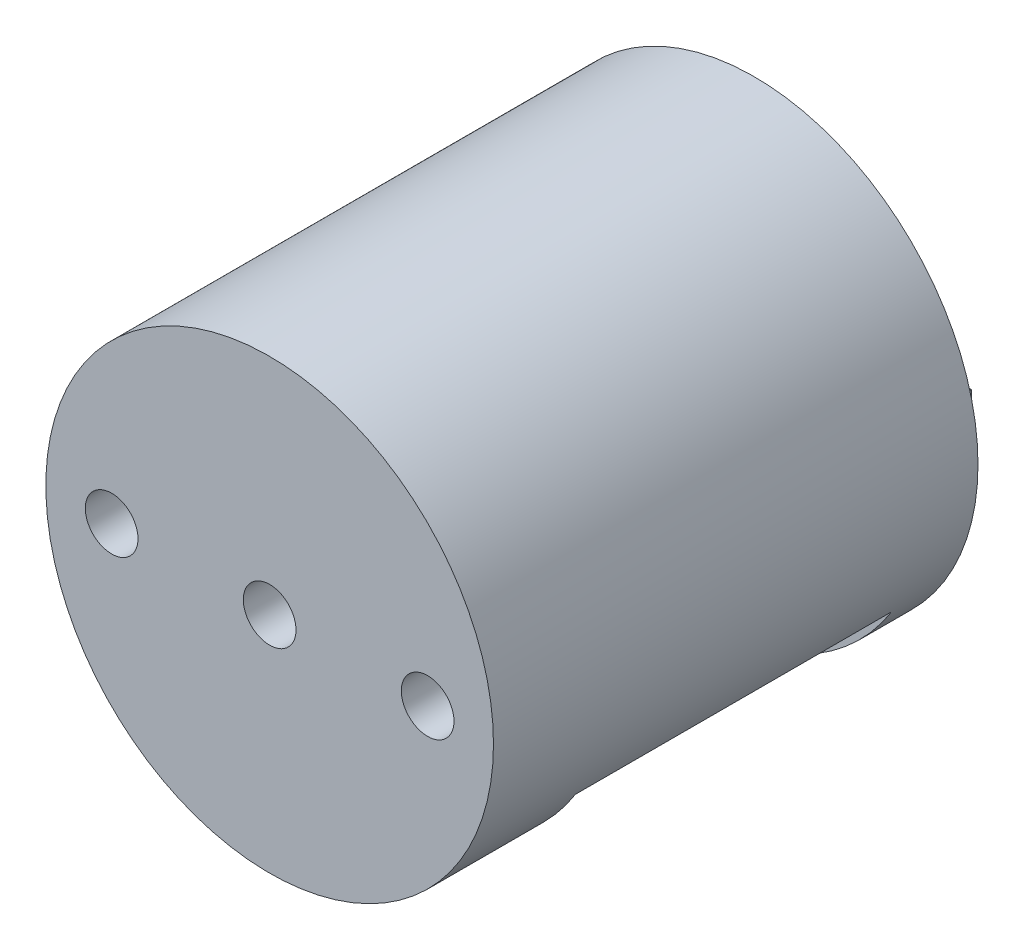
SolidWorks part; units mm, degrees
ref_plane "Plan de face" through (0, 0, 0) normal (0, 0, 1) x (1, 0, 0)
ref_plane "Plan de dessus" through (0, 0, 0) normal (0, 1, 0) x (1, 0, 0)
ref_plane "Plan de droite" through (0, 0, 0) normal (1, 0, 0) x (0, 0, -1)
sketch "Esquisse1" plane through (0, 0, 0) normal (0, 0, 1) x (1, 0, 0)
  circle A0 centre (0, 0) radius 8.5
extrude "Boss.-Extru.1" add sketch "Esquisse1" along normal blind 18.4
sketch "Esquisse2" plane through (0, 0, 0) normal (0, 0, -1) x (-1, 0, 0)
  line L1 (-3.2, -2.6) -> (3.2, -2.6)
  line L2 (-3.2, -2.6) -> (-3.2, -6)
  line L3 (-3.2, -6) -> (3.2, -6)
  line L4 (3.2, -2.6) -> (3.2, -6)
  dimension "D1" = 6.4
  dimension "D2" = 3.4
  dimension "D3" = 3.2
  dimension "D4" = 6
extrude "Boss.-Extru.2" add sketch "Esquisse2" along normal blind 2.6
sketch "Esquisse3" plane through (0, 0, -2.6) normal (0, 0, -1) x (-1, 0, 0)
  line L0 (-1.48, -3.1652) -> (-0.98, -3.1652)
  line L1 (-2.75, -3.1652) -> (-2.25, -3.1652)
  line L2 (-2.75, -3.1652) -> (-2.75, -3.6652)
  line L3 (-2.75, -3.6652) -> (-2.25, -3.6652)
  line L4 (-2.25, -3.1652) -> (-2.25, -3.6652)
  line L5 (-1.48, -3.1652) -> (-1.48, -3.6652)
  line L6 (-1.48, -3.6652) -> (-0.98, -3.6652)
  line L7 (-0.98, -3.1652) -> (-0.98, -3.6652)
  line L8 (-0.21, -3.1652) -> (0.29, -3.1652)
  line L9 (-0.21, -3.1652) -> (-0.21, -3.6652)
  line L10 (-0.21, -3.6652) -> (0.29, -3.6652)
  line L11 (0.29, -3.1652) -> (0.29, -3.6652)
  line L12 (1.06, -3.1652) -> (1.56, -3.1652)
  line L13 (1.06, -3.1652) -> (1.06, -3.6652)
  line L14 (1.06, -3.6652) -> (1.56, -3.6652)
  line L15 (1.56, -3.1652) -> (1.56, -3.6652)
  line L16 (2.33, -3.1652) -> (2.83, -3.1652)
  line L17 (2.33, -3.1652) -> (2.33, -3.6652)
  line L18 (2.33, -3.6652) -> (2.83, -3.6652)
  line L19 (2.83, -3.1652) -> (2.83, -3.6652)
  line L20 (-2.75, -4.4352) -> (-2.25, -4.4352)
  line L21 (-2.75, -4.4352) -> (-2.75, -4.9352)
  line L22 (-2.75, -4.9352) -> (-2.25, -4.9352)
  line L23 (-2.25, -4.4352) -> (-2.25, -4.9352)
  line L24 (-1.48, -4.4352) -> (-0.98, -4.4352)
  line L25 (-1.48, -4.4352) -> (-1.48, -4.9352)
  line L26 (-1.48, -4.9352) -> (-0.98, -4.9352)
  line L27 (-0.98, -4.4352) -> (-0.98, -4.9352)
  line L28 (-0.21, -4.4352) -> (0.29, -4.4352)
  line L29 (-0.21, -4.4352) -> (-0.21, -4.9352)
  line L30 (-0.21, -4.9352) -> (0.29, -4.9352)
  line L31 (0.29, -4.4352) -> (0.29, -4.9352)
  line L32 (1.06, -4.4352) -> (1.56, -4.4352)
  line L33 (1.06, -4.4352) -> (1.06, -4.9352)
  line L34 (1.06, -4.9352) -> (1.56, -4.9352)
  line L35 (1.56, -4.4352) -> (1.56, -4.9352)
  line L36 (2.33, -4.4352) -> (2.83, -4.4352)
  line L37 (2.33, -4.4352) -> (2.33, -4.9352)
  line L38 (2.33, -4.9352) -> (2.83, -4.9352)
  line L39 (2.83, -4.4352) -> (2.83, -4.9352)
  line L40 (-3.2, -2.6) -> (-3.2, -6) construction
  dimension "D1" = 0.5
  dimension "D2" = 5
  dimension "D4" = 0.45
  dimension "D3" = 2
extrude "Boss.-Extru.3" add sketch "Esquisse3" along normal blind 3
chamfer "Chanfrein1" distance 0.1 angle 45 40 edges at (2.5, -3.1652, -5.6) (2.25, -3.4152, -5.6) (2.5, -3.6652, -5.6) (2.75, -3.4152, -5.6) (2.5, -4.4352, -5.6) (2.25, -4.6852, -5.6) (2.5, -4.9352, -5.6) (2.75, -4.6852, -5.6) (1.23, -3.1652, -5.6) (0.98, -3.4152, -5.6) (1.23, -3.6652, -5.6) (1.48, -3.4152, -5.6) (1.23, -4.4352, -5.6) (0.98, -4.6852, -5.6) (1.23, -4.9352, -5.6) (1.48, -4.6852, -5.6) (-0.04, -3.1652, -5.6) (-0.29, -3.4152, -5.6) (-0.04, -3.6652, -5.6) (0.21, -3.4152, -5.6) (-0.04, -4.4352, -5.6) (-0.29, -4.6852, -5.6) (-0.04, -4.9352, -5.6) (0.21, -4.6852, -5.6) (-1.31, -3.1652, -5.6) (-1.56, -3.4152, -5.6) (-1.31, -3.6652, -5.6) (-1.06, -3.4152, -5.6) (-1.31, -4.4352, -5.6) (-1.56, -4.6852, -5.6) (-1.31, -4.9352, -5.6) (-1.06, -4.6852, -5.6) (-2.58, -3.1652, -5.6) (-2.83, -3.4152, -5.6) (-2.58, -3.6652, -5.6) (-2.33, -3.4152, -5.6) (-2.58, -4.4352, -5.6) (-2.83, -4.6852, -5.6) (-2.58, -4.9352, -5.6) (-2.33, -4.6852, -5.6)
ref_plane "Plan1" through (8.5, 0, 0) normal (1, 0, 0) x (0, 0, -1)
sketch "Esquisse4" plane through (8.5, 0, 0) normal (1, 0, 0) x (0, 0, -1)
  line L0 (-18.4, -8.5) -> (0, -8.5) construction
  line L1 (-14, -4.5) -> (-2, -4.5)
  line L2 (-14, -4.5) -> (-14, -8.5)
  line L3 (-14, -8.5) -> (-2, -8.5)
  line L4 (-2, -4.5) -> (-2, -8.5)
  line L5 (0, -8.5) -> (0, 8.5) construction
  dimension "D1" = 12
  dimension "D2" = 2
  dimension "D3" = 4
extrude "Enlèv. mat.-Extru.1" cut sketch "Esquisse4" against normal through all
sketch "Esquisse5" plane through (0, 0, 18.4) normal (0, 0, 1) x (1, 0, 0)
  circle A0 centre (-6, 0) radius 1
  circle A1 centre (6, 0) radius 1
  dimension "D1" = 6
  dimension "D2" = 6
  dimension "D3" = 2
  dimension "D4" = 2
extrude "Enlèv. mat.-Extru.2" cut sketch "Esquisse5" against normal blind 5
sketch "Esquisse6" plane through (0, 0, 2) normal (0, 0, 1) x (1, 0, 0)
  circle A0 centre (0, 0) radius 6.4931
extrude "Enlèv. mat.-Extru.3" cut sketch "Esquisse6" along normal blind 12.5 and the other way blind 0.5
sketch "Esquisse7" plane through (0, 0, 1.5) normal (0, 0, 1) x (1, 0, 0)
  circle A0 centre (0, 0) radius 2.5
extrude "Boss.-Extru.4" add sketch "Esquisse7" along normal blind 5
sketch "Esquisse8" plane through (0, 0, 6.5) normal (0, 0, 1) x (1, 0, 0)
  circle A0 centre (0, 0) radius 6
extrude "Boss.-Extru.5" add sketch "Esquisse8" along normal blind 0.5
sketch "Esquisse10" plane through (0, 0, 18.4) normal (0, 0, 1) x (1, 0, 0)
  circle A0 centre (0, 0) radius 1
extrude "Enlèv. mat.-Extru.4" cut sketch "Esquisse10" against normal blind 10
